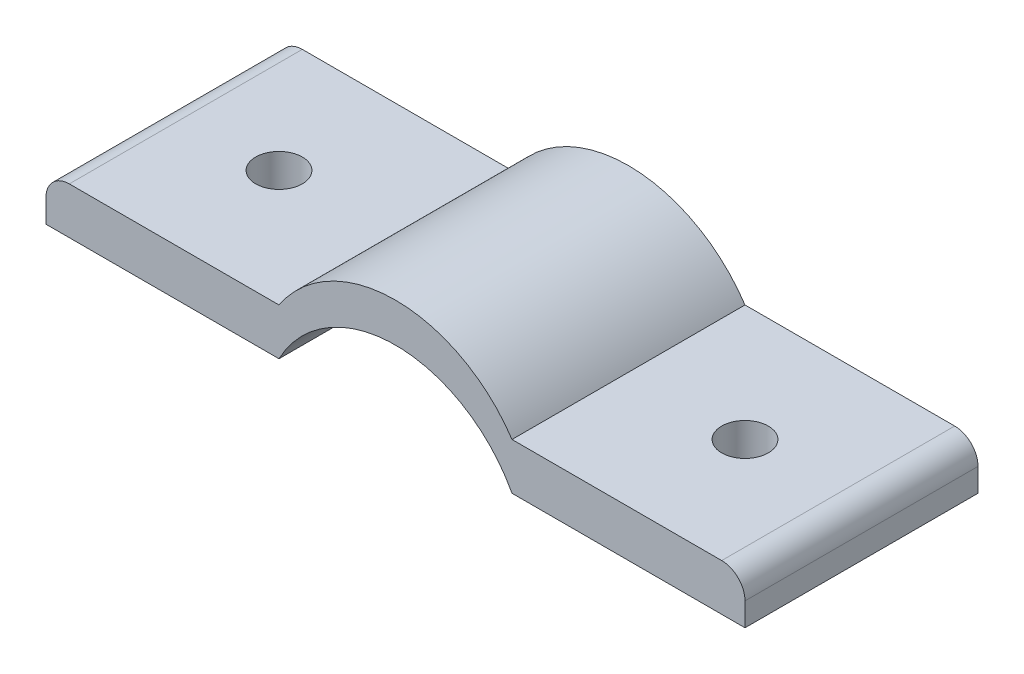
SolidWorks part; units mm, degrees
ref_plane "Front Plane" through (0, 0, 0) normal (0, 0, 1) x (1, 0, 0)
ref_plane "Top Plane" through (0, 0, 0) normal (0, 1, 0) x (1, 0, 0)
ref_plane "Right Plane" through (0, 0, 0) normal (1, 0, 0) x (0, 0, -1)
sketch "Sketch1" plane through (0, 0, 0) normal (0, 0, 1) x (1, 0, 0)
  line L0 (-24.7059, -2.5735) -> (-14.7059, -2.5735)
  line L5 (-4.7059, -2.5735) -> (5.2941, -2.5735)
  line L6 (-24.7059, -2.5735) -> (-24.7059, -0.5735)
  line L7 (-24.7059, -0.5735) -> (-14.7059, -0.5735)
  line L8 (5.2941, -2.5735) -> (5.2941, -0.5735)
  line L9 (5.2941, -0.5735) -> (-4.7059, -0.5735)
  arc A0 (-14.7059, -2.5735) -> (-4.7059, -2.5735) centre (-9.7059, -5.2249) cw
  arc A1 (-14.7059, -0.5735) -> (-4.7059, -0.5735) centre (-9.7059, -3.8966) cw
  point P3 (0, 0)
  point P4 (0, 0)
  dimension "D1" = 10
  dimension "D2" = 10
  dimension "D6" = 10
  dimension "D7" = 2
  dimension "D8" = 10
  dimension "D9" = 2
extrude "Boss-Extrude1" add sketch "Sketch1" along normal blind 10
sketch "Sketch2" plane through (0, -0.5735, 0) normal (0, 1, 0) x (1, 0, 0)
  line L0 (5.2941, 0) -> (-4.7059, 0) construction
  line L1 (5.2941, -10) -> (5.2941, 0) construction
  line L2 (-14.7059, 0) -> (-24.7059, 0) construction
  line L4 (-24.7059, -10) -> (-24.7059, 0) construction
  circle A0 centre (0.2941, -5) radius 1
  circle A1 centre (-19.7059, -5) radius 1
  dimension "D1" = 5
  dimension "D2" = 5
  dimension "D3" = 5
  dimension "D4" = 5
extrude "Cut-Extrude1" cut sketch "Sketch2" against normal blind 10
fillet "Fillet1" radius 1 2 edges at (5.2941, -0.5735, 5) (-24.7059, -0.5735, 5)
